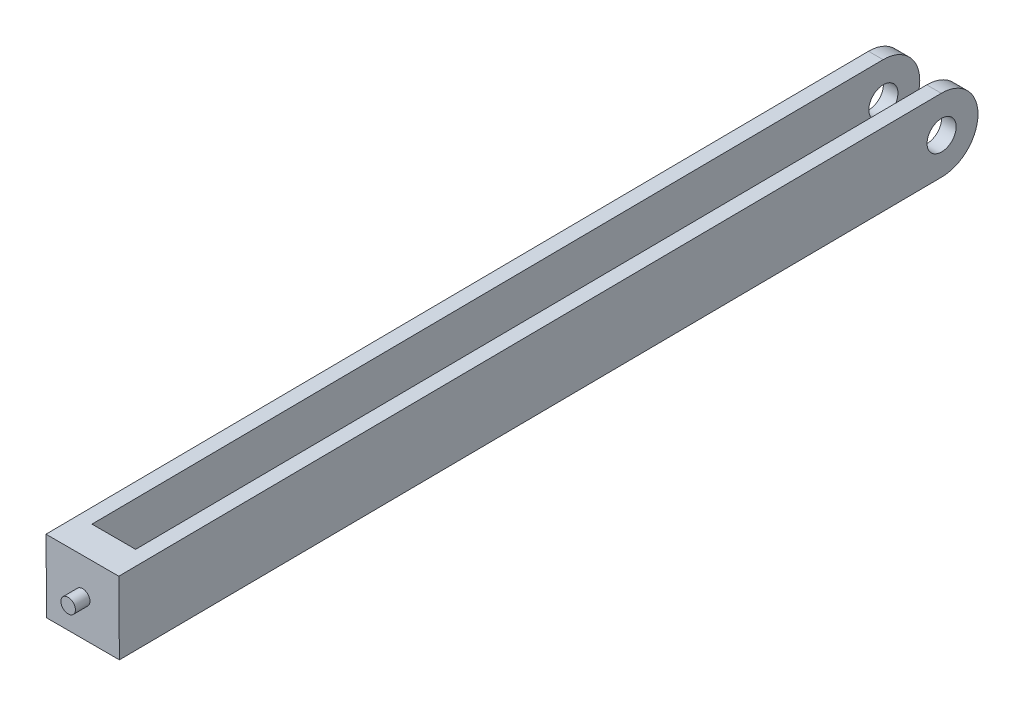
SolidWorks part; units mm, degrees
ref_plane "Front Plane" through (0, 0, 0) normal (0, 0, 1) x (1, 0, 0)
ref_plane "Top Plane" through (0, 0, 0) normal (0, 1, 0) x (1, 0, 0)
ref_plane "Right Plane" through (0, 0, 0) normal (1, 0, 0) x (0, 0, -1)
sketch "Sketch1" plane through (0, 0, 0) normal (1, 0, 0) x (0, 0, -1)
  line L0 (-150.4467, 6.4875) -> (149.5533, 9.0332) construction
  line L1 (-150.5528, 18.987) -> (149.4472, 21.5327)
  line L2 (-150.3406, -6.0121) -> (149.6594, -3.4664)
  arc A0 (-150.5528, 18.987) -> (-150.3406, -6.0121) centre (-150.4467, 6.4875) ccw
  arc A1 (149.6594, -3.4664) -> (149.4472, 21.5327) centre (149.5533, 9.0332) ccw
  circle A2 centre (149.5533, 9.0332) radius 5
  point P2 (-0.4467, 7.7603)
  dimension "D2" = 10
  dimension "D3" = 12.5
  dimension "D1" = 300
extrude "Boss-Extrude1" add sketch "Sketch1" along normal blind 25
sketch "Sketch2" plane through (0, 0, 0) normal (0, 1, 0) x (1, 0, 0)
  line L0 (0, 162.0533) -> (0, 149.4472) construction
  line L1 (5, 167.7384) -> (20, 167.7384)
  line L2 (5, 167.7384) -> (5, -122.2616)
  line L3 (5, -122.2616) -> (20, -122.2616)
  line L4 (20, 167.7384) -> (20, -122.2616)
  dimension "D1" = 15
  dimension "D2" = 5
  dimension "D3" = 290
extrude "Cut-Extrude1" cut sketch "Sketch2" along normal blind 35 and the other way blind 15
sketch "Sketch3" plane through (25, 0, 0) normal (1, 0, 0) x (0, 0, -1)
  circle A0 centre (-150.4467, 6.4875) radius 5
  arc A1 (-150.5528, 18.987) -> (-150.3406, -6.0121) centre (-150.4467, 6.4875) ccw construction
  dimension "D1" = 10
  dimension "D2" = 0
extrude "Cut-Extrude4" cut sketch "Sketch3" against normal blind 40
ref_plane "Plane1" through (0, -1.3821, 162.8804) normal (0, -0.0085, 1) x (1, 0, 0)
sketch "Sketch7" plane through (0, -1.3821, 162.8804) normal (0, -0.0085, 1) x (1, 0, 0)
  line L0 (25, -4.7362) -> (25, 20.2638) construction
  line L2 (25, 21.3373) -> (25, -7.3274)
  line L6 (0, 21.3373) -> (0, -7.3274)
  line L9 (25, 21.3373) -> (0, 21.3373)
  line L10 (0, -7.3274) -> (25, -7.3274)
  dimension "D2" = 0
extrude "Cut-Extrude7" cut sketch "Sketch7" against normal blind 30
sketch "Sketch9" plane through (0, -1.1276, 132.8814) normal (0, -0.0085, 1) x (1, 0, 0)
  line L0 (0, -4.7362) -> (25, -4.7362) construction
  line L1 (0, 20.2638) -> (0, -4.7362) construction
  circle A0 centre (12.5, 7.7638) radius 2.5
  dimension "D1" = 5
  dimension "D2" = 12.5
  dimension "D3" = 12.5
extrude "Boss-Extrude3" add sketch "Sketch9" along normal blind 5
